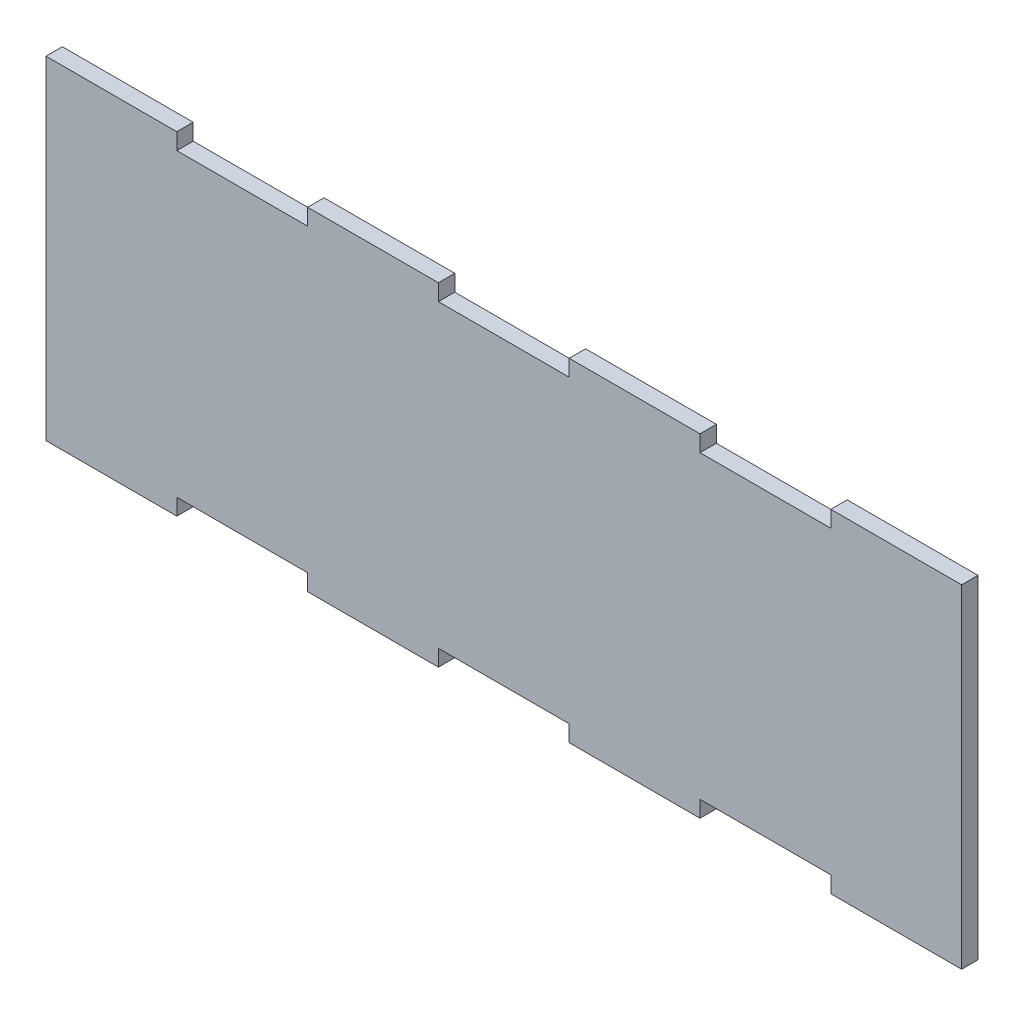
SolidWorks part; units mm, degrees
ref_plane "Front Plane" through (0, 0, 0) normal (0, 0, 1) x (1, 0, 0)
ref_plane "Top Plane" through (0, 0, 0) normal (0, 1, 0) x (1, 0, 0)
ref_plane "Right Plane" through (0, 0, 0) normal (1, 0, 0) x (0, 0, -1)
sketch "Sketch1" plane through (0, 0, 0) normal (0, 0, 1) x (1, 0, 0)
  line L1 (-69.85, -25.4) -> (69.85, -25.4)
  line L2 (-69.85, -25.4) -> (-69.85, 25.4)
  line L3 (-69.85, 25.4) -> (69.85, 25.4)
  line L4 (69.85, -25.4) -> (69.85, 25.4)
  line L5 (-69.85, -25.4) -> (69.85, 25.4) construction
  line L6 (-69.85, 25.4) -> (69.85, -25.4) construction
  point P0 (0, 0)
  dimension "D1" = 50.8
  dimension "D2" = 139.7
extrude "Boss-Extrude1" add sketch "Sketch1" along normal blind 2.5
sketch "Sketch3" plane through (0, 0, 0) normal (0, 0, -1) x (-1, 0, 0)
  line L0 (-69.85, 22.9) -> (69.85, 22.9) construction
  line L1 (-69.85, -25.4) -> (-69.85, 25.4) construction
  line L2 (69.85, 25.4) -> (69.85, -25.4) construction
  line L3 (-69.85, -22.9) -> (69.85, -22.9) construction
  line L4 (-69.85, 25.4) -> (69.85, 25.4) construction
  line L5 (69.85, -25.4) -> (-69.85, -25.4) construction
  line L6 (-69.85, 22.9) -> (-49.8929, 22.9) construction
  line L7 (-49.8929, 25.4) -> (-29.9357, 25.4)
  line L8 (-49.8929, 25.4) -> (-49.8929, 22.9)
  line L9 (-49.8929, 22.9) -> (-29.9357, 22.9)
  line L10 (-29.9357, 25.4) -> (-29.9357, 22.9)
  line L11 (-9.9786, 25.4) -> (9.9786, 25.4)
  line L12 (-9.9786, 25.4) -> (-9.9786, 22.9)
  line L13 (-9.9786, 22.9) -> (9.9786, 22.9)
  line L14 (9.9786, 25.4) -> (9.9786, 22.9)
  line L15 (29.9357, 25.4) -> (49.8929, 25.4)
  line L16 (29.9357, 25.4) -> (29.9357, 22.9)
  line L17 (29.9357, 22.9) -> (49.8929, 22.9)
  line L18 (49.8929, 25.4) -> (49.8929, 22.9)
  line L19 (-29.9357, 22.9) -> (-9.9786, 22.9) construction
  line L20 (9.9786, 22.9) -> (29.9357, 22.9) construction
  line L21 (49.8929, 22.9) -> (69.85, 22.9) construction
  line L22 (-69.85, 25.4) -> (-49.8929, 25.4) construction
  line L23 (-29.9357, 25.4) -> (-9.9786, 25.4) construction
  line L24 (9.9786, 25.4) -> (29.9357, 25.4) construction
  line L25 (49.8929, 25.4) -> (69.85, 25.4) construction
  line L26 (-69.85, -25.4) -> (-49.8929, -25.4) construction
  line L27 (-49.8929, -22.9) -> (-29.9357, -22.9)
  line L28 (-49.8929, -22.9) -> (-49.8929, -25.4)
  line L29 (-49.8929, -25.4) -> (-29.9357, -25.4)
  line L30 (-29.9357, -22.9) -> (-29.9357, -25.4)
  line L31 (-9.9786, -22.9) -> (9.9786, -22.9)
  line L32 (-9.9786, -22.9) -> (-9.9786, -25.4)
  line L33 (-9.9786, -25.4) -> (9.9786, -25.4)
  line L34 (9.9786, -22.9) -> (9.9786, -25.4)
  line L35 (29.9357, -22.9) -> (49.8929, -22.9)
  line L36 (29.9357, -22.9) -> (29.9357, -25.4)
  line L37 (29.9357, -25.4) -> (49.8929, -25.4)
  line L38 (49.8929, -22.9) -> (49.8929, -25.4)
  line L39 (-29.9357, -25.4) -> (-9.9786, -25.4) construction
  line L40 (9.9786, -25.4) -> (29.9357, -25.4) construction
  line L41 (49.8929, -25.4) -> (69.85, -25.4) construction
  dimension "D1" = 2.5
  dimension "D2" = 2.5
extrude "Cut-Extrude2" cut sketch "Sketch3" against normal blind 2.54
